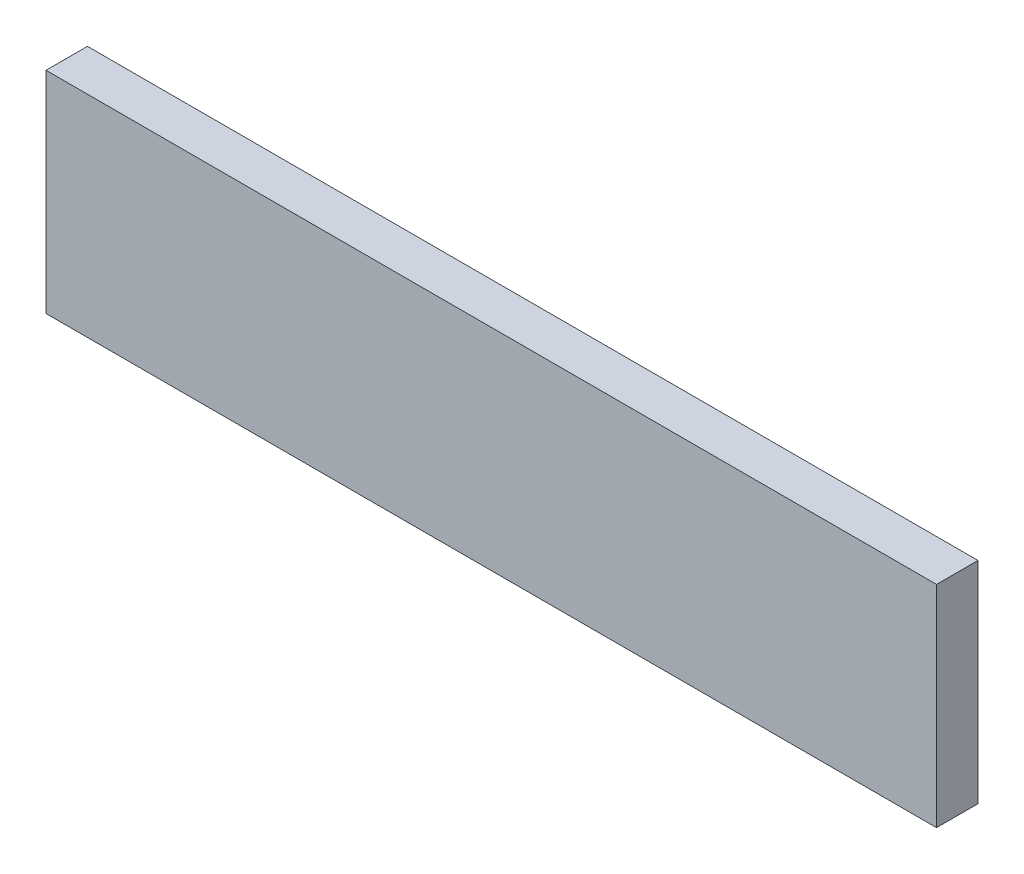
SolidWorks part; units mm, degrees
material "轻木"
ref_plane "Front" through (0, 0, 0) normal (0, 0, 1) x (1, 0, 0)
ref_plane "Top" through (0, 0, 0) normal (0, 1, 0) x (1, 0, 0)
ref_plane "Right" through (0, 0, 0) normal (1, 0, 0) x (0, 0, -1)
sketch "草图1" plane through (0, 0, 0) normal (0, 0, 1) x (1, 0, 0)
  line L1 (0, 0) -> (322.1, 0)
  line L2 (0, 0) -> (0, 76.2)
  line L3 (0, 76.2) -> (322.1, 76.2)
  line L4 (322.1, 0) -> (322.1, 76.2)
  dimension "D1" = 322.1
  dimension "D2" = 76.2
extrude "凸台-拉伸1" add sketch "草图1" along normal blind 15
